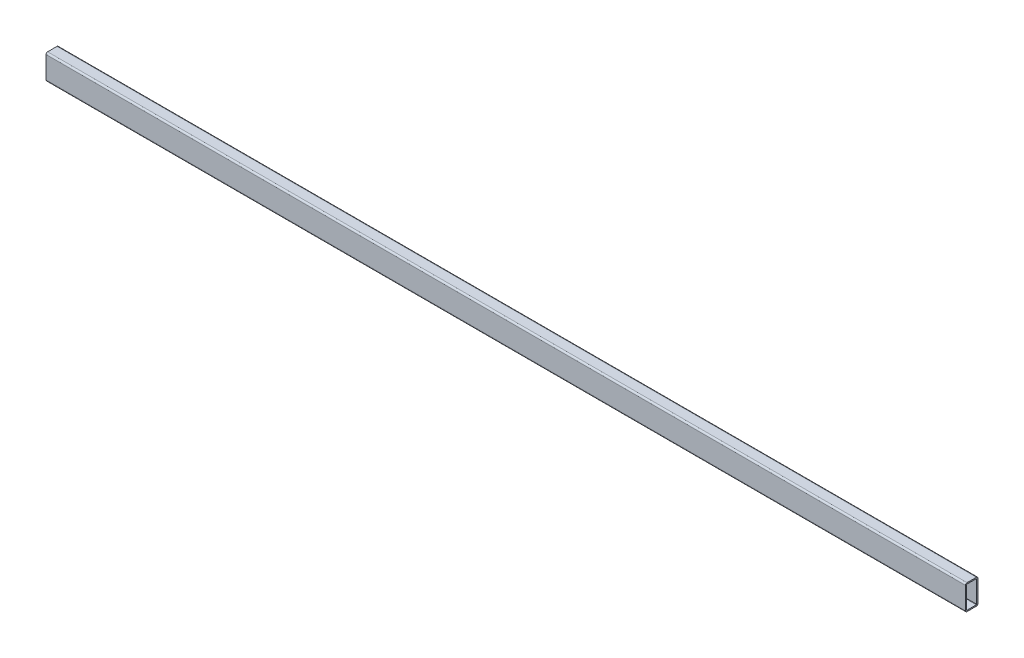
SolidWorks part; units mm, degrees
material "Ст 3 ГОСТ 380-88"
ref_plane "Front Plane" through (0, 0, 0) normal (0, 0, 1) x (1, 0, 0)
ref_plane "Top Plane" through (0, 0, 0) normal (0, 1, 0) x (1, 0, 0)
ref_plane "Right Plane" through (0, 0, 0) normal (1, 0, 0) x (0, 0, -1)
sketch "Sketch12" plane through (0, 0, 0) normal (0, 0, 1) x (1, 0, 0)
  line L0 (-732.5, 0) -> (732.5, 0)
  dimension "D1" = 1465
other "Rectangular tube - configured 60 X 40 X 3.2(2)"
ref_plane "Plane5" through (-732.5, 0, 0) normal (1, 0, 0) x (0, 1, 0)
sketch "Sketch1" plane through (-732.5, 0, 0) normal (1, 0, 0) x (0, 1, 0)
  line L0 (-17.5, -8) -> (17.5, -8)
  line L1 (-18, -7.5) -> (-18, 7.5)
  line L2 (17.5, 8) -> (-17.5, 8)
  line L3 (18, 7.5) -> (18, -7.5)
  line L4 (-17.5, -10) -> (17.5, -10)
  line L5 (-20, -7.5) -> (-20, 7.5)
  line L6 (17.5, 10) -> (-17.5, 10)
  line L7 (20, 7.5) -> (20, -7.5)
  arc A0 (20, 7.5) -> (17.5, 10) centre (17.5, 7.5) ccw
  arc A1 (17.5, -10) -> (20, -7.5) centre (17.5, -7.5) ccw
  arc A2 (-20, -7.5) -> (-17.5, -10) centre (-17.5, -7.5) ccw
  arc A3 (-17.5, 10) -> (-20, 7.5) centre (-17.5, 7.5) ccw
  arc A4 (-17.5, 8) -> (-18, 7.5) centre (-17.5, 7.5) ccw
  arc A5 (18, 7.5) -> (17.5, 8) centre (17.5, 7.5) ccw
  arc A6 (17.5, -8) -> (18, -7.5) centre (17.5, -7.5) ccw
  arc A7 (-18, -7.5) -> (-17.5, -8) centre (-17.5, -7.5) ccw
  point P0 (0, 10)
  point P1 (20, 0)
  point P2 (0, -10)
  point P3 (-20, 0)
  point P4 (-20, 10)
  point P5 (20, 10)
  point P6 (20, -10)
  point P7 (-20, -10)
  point P8 (0, 0)
  point P33 (0, 0)
  dimension "D1" = 2.5
  dimension "Thickness" = 2
  dimension "V_leg" = 20
  dimension "H_leg" = 40
sketch "Sketch13" [suppressed] plane through (0, 20, 0) normal (0, 1, 0) x (1, 0, 0)
  line L0 (340, -23.6) -> (-340, -23.6) construction
  line L2 (-146.967, -23.6) -> (-148.4014, -20.9651)
  line L8 (-77.9742, -23.6) -> (-75.3275, -22.1877)
  spline S3 degree 5 poles (-1495.764, 2640.3207) (-54.553, -70.7255) (-171.9433, 151.7914) (-124.9932, 64.4419) (-90.2809, -0.4141) (-58.6075, -59.9528) (-57.0332, -62.9132) (-50.8072, -74.6241) (-44.8114, -85.9169) (-40.4158, -94.2031) (-34.6955, -104.9963) (-29.2334, -115.3147) (-27.9081, -117.8187) (-6.1309, -158.9794) (9.5785, -188.8602) (45.0801, -256.14) (-220.7139, 245.2426) (1397.5545, -2793.1722) knots -593.265604 -593.265604 -593.265604 -593.265604 -593.265604 -593.265604 111.1559 111.1559 111.1559 148.187473 148.187473 148.187473 259.213082 259.213082 259.213082 296.361016 296.361016 296.361016 871.835515 871.835515 871.835515 871.835515 871.835515 871.835515 weights 1 1 1 1 1 1 1 1 1 1 1 1 1 1 1 1 1 1 only from (-86.3756, -7.8668) to (-13.0552, -145.9241) construction
  spline S4 degree 5 poles (-2891.5119, 1081.1487) (142.8151, 263.2412) (-50.9894, -103.5827) (-137.1222, -44.038) (-122.2566, -1.9712) (-100.2843, 0.1197) (-99.3189, 0.1331) (-97.3976, 0.0041) (-95.5308, -0.4278) (-94.6201, -0.7173) (-92.4201, -1.6144) (-90.4526, -2.9143) (-89.3782, -3.8223) (-82.0749, -11.5923) (-82.3869, -24.5188) (-91.346, -33.6867) (-134.8623, 15.5931) (1509.7915, -2547.4591) knots -234.55056 -234.55056 -234.55056 -234.55056 -234.55056 -234.55056 11.238702 11.238702 11.238702 22.477403 22.477403 22.477403 33.716105 33.716105 33.716105 50.576238 50.576238 50.576238 162.81808 162.81808 162.81808 162.81808 162.81808 162.81808 weights 1 1 1 1 1 1 1 1 1 1 1 1 1 1 1 1 1 1 only from (-106.705, -1.7175) to (-86.3756, -7.8668) construction
  spline S5 degree 5 poles (-2864.2984, -1509.6725) (-276.3602, -94.7125) (-345.1875, -132.0922) (-303.3863, -109.1241) (-254.2395, -82.166) (-202.7549, -54.0301) (-200.2583, -52.6659) (-192.7828, -48.5821) (-185.2556, -44.4723) (-180.2173, -41.7225) (-170.1251, -36.2168) (-159.9585, -30.6752) (-154.883, -27.9099) (-33.4803, 38.2018) (92.7831, 106.1794) (200.5046, 162.8586) (275.2579, 193.0138) (2464.1913, 1543.5518) knots -550.303408 -550.303408 -550.303408 -550.303408 -550.303408 -550.303408 62.724665 62.724665 62.724665 93.899246 93.899246 93.899246 155.902112 155.902112 155.902112 217.55572 217.55572 217.55572 1627.442536 1627.442536 1627.442536 1627.442536 1627.442536 1627.442536 weights 1 1 1 1 1 1 1 1 1 1 1 1 1 1 1 1 1 1 only from (-232.4669, -70.2789) to (-106.705, -1.7175) construction
  spline S6 degree 5 poles (-86.3756, -7.8668) (-84.6836, -11.0331) (-82.9975, -14.1895) (-81.3168, -17.337) (-79.6421, -20.4743) (-77.9742, -23.6) knots 0 0 0 0 0 0 37.291521 37.291521 37.291521 37.291521 37.291521 37.291521 weights 1 1 1 1 1 1
  spline S7 degree 5 poles (-106.705, -1.7175) (-105.8638, -1.2611) (-104.1041, -0.4804) (-102.2198, 0.0152) (-100.2796, 0.1976) (-97.3976, 0.0041) (-95.5308, -0.4278) (-94.6201, -0.7173) (-92.4201, -1.6144) (-90.4526, -2.9143) (-89.3782, -3.8223) (-88.1065, -5.1752) (-87.0657, -6.6845) (-86.8204, -7.0708) (-86.5903, -7.4651) (-86.3756, -7.8668) knots 0 0 0 0 0 0 11.238702 22.477403 22.477403 22.477403 33.716105 33.716105 33.716105 50.576238 50.576238 50.576238 56.195589 56.195589 56.195589 56.195589 56.195589 56.195589 weights 1 1 1 1 1 1 1 1 1 1 1 1 1 1 1 1
  spline S8 degree 5 poles (-146.967, -23.6) (-146.514, -23.3534) (-146.061, -23.1068) (-145.6079, -22.8602) (-137.585, -18.4931) (-129.5409, -14.118) (-121.9372, -9.9855) (-114.3244, -5.8515) (-106.705, -1.7175) knots 212.071321 212.071321 212.071321 212.071321 212.071321 212.071321 217.55572 217.55572 217.55572 309.169876 309.169876 309.169876 309.169876 309.169876 309.169876 weights 1 1 1 1 1 1 1 1 1
  spline S9 degree 1 poles (-148.4014, -20.9651) (-108.1357, 0.9194) knots 0 0 1 1 construction
  spline S10 degree 3 poles (-148.4014, -20.9651) (-145.0557, -19.1438) (-138.3692, -15.5051) (-128.3056, -10.033) (-118.2289, -4.5585) (-111.4994, -0.9057) (-108.1357, 0.9194) knots 212.071321 212.071321 212.071321 212.071321 236.34596 260.620598 284.895237 309.169876 309.169876 309.169876 309.169876
  spline S11 degree 1 poles (-108.1357, 0.9194) (-83.7297, -6.4528) knots 0 0 1 1 construction
  spline S12 degree 3 poles (-108.1357, 0.9194) (-106.0371, 2.058) (-101.326, 3.5036) (-94.0109, 2.7036) (-87.7202, -0.8096) (-84.8056, -4.4396) (-83.7297, -6.4528) knots 0 0 0 0 14.048897 28.097794 42.146692 56.195589 56.195589 56.195589 56.195589
  spline S13 degree 1 poles (-83.7297, -6.4528) (-75.3275, -22.1877) knots 0 0 1 1 construction
  spline S14 degree 3 poles (-83.7297, -6.4528) (-83.0258, -7.7702) (-81.6164, -10.4081) (-79.5128, -14.3468) (-77.4147, -18.2765) (-76.0238, -20.8828) (-75.3275, -22.1877) knots 0 0 0 0 9.32288 18.64576 27.968641 37.291521 37.291521 37.291521 37.291521
  dimension "D1" = 3
extrude "Boss-Extrude1" [suppressed] add sketch "Sketch13" along normal blind 10 separate body contours S14 S12 S10 L2 S8 S7 S6 L8
mirror "Mirror3" [suppressed] about plane through (0, 0, 0) normal (1, 0, 0)
sketch "Sketch17" [suppressed] plane through (0, 0, 10) normal (0, 0, 1) x (1, 0, 0)
  line B0 (499.0524, 17.2686) -> (501.1488, 2.4943)
  line B1 (501.1488, 2.4943) -> (677.1776, 7.2235)
sketch_block_instance "Block1-1"
sketch_block "Block1"
extrude "Extrude-Thin1" [suppressed] add sketch "Sketch17" along normal blind 5 separate body thin
pattern_linear "LPattern1" [suppressed] count 4 spacing 350
